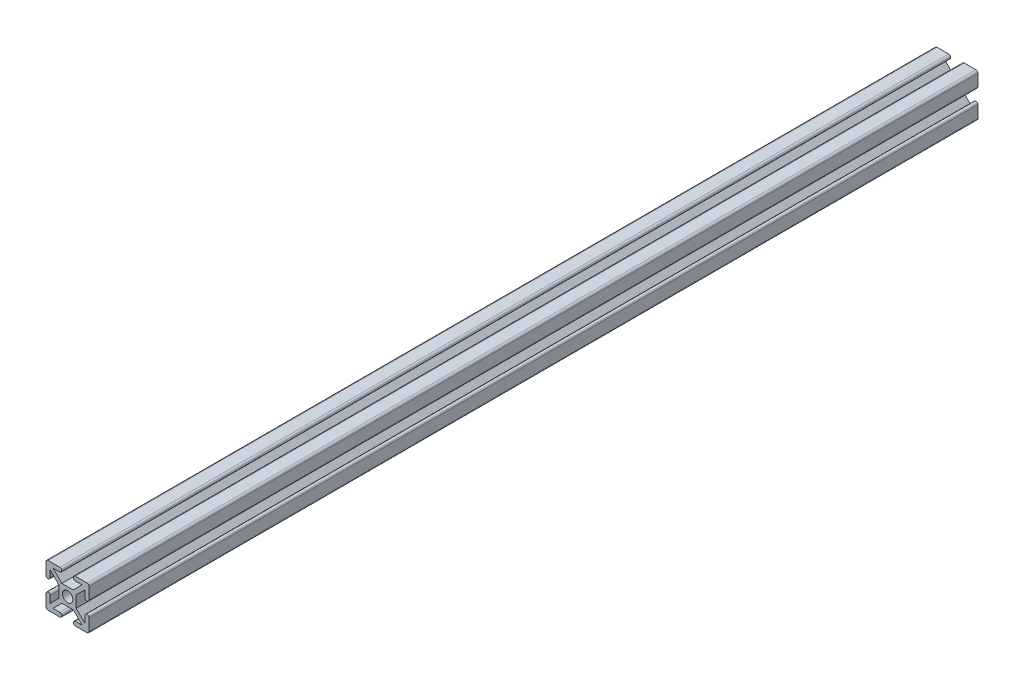
SolidWorks part; units mm, degrees
ref_plane "Alzado" through (0, 0, 0) normal (0, 0, 1) x (1, 0, 0)
ref_plane "Planta" through (0, 0, 0) normal (0, 1, 0) x (1, 0, 0)
ref_plane "Vista lateral" through (0, 0, 0) normal (1, 0, 0) x (0, 0, -1)
sketch "Croquis1" plane through (0, 0, 0) normal (0, 0, 1) x (1, 0, 0)
  line L0 (-16.9501, 14.578) -> (-16.9501, 16.003) construction
  line L1 (2.1027, -1.572) -> (6.8277, -1.572)
  line L2 (-18.3751, 24.153) -> (-18.3751, 16.003)
  line L3 (-16.9501, 25.578) -> (-8.8001, 25.578)
  line L4 (2.0499, 25.578) -> (10.1999, 25.578)
  line L5 (-13.4723, -1.572) -> (-8.7473, -1.572)
  line L6 (-9.3751, 14.578) -> (-9.3751, 6.578)
  line L7 (-18.3223, 5.153) -> (-18.3223, -2.997)
  line L8 (-16.9237, -4.3955) -> (-8.7473, -4.422)
  line L9 (11.6249, 24.153) -> (11.6249, 16.1067)
  line L10 (-15.5251, 20.728) -> (-15.5251, 16.003)
  line L11 (11.6249, 5.2567) -> (11.6249, -2.997)
  line L12 (-7.3751, 24.153) -> (-8.8001, 24.153) construction
  line L13 (2.1027, -4.422) -> (10.1999, -4.422)
  line L14 (-13.5251, 22.728) -> (-8.8001, 22.728)
  line L15 (-15.5251, 5.153) -> (-15.5251, 0.428)
  line L16 (0.6249, 24.153) -> (2.0499, 24.153) construction
  line L17 (2.0499, 22.728) -> (6.7749, 22.728)
  line L18 (10.1999, 14.6817) -> (10.1999, 16.1067) construction
  line L19 (-7.3751, 16.578) -> (-13.5251, 22.728)
  line L20 (8.7749, 20.728) -> (8.7749, 16.1067)
  line L21 (10.1999, 6.6817) -> (10.1999, 5.2567) construction
  line L22 (-9.3751, 14.578) -> (-15.5251, 20.728)
  line L23 (8.7749, 5.2567) -> (8.7749, 0.428)
  line L24 (0.6777, -2.997) -> (2.1027, -2.997) construction
  line L25 (-9.3751, 6.578) -> (-15.5251, 0.428)
  line L26 (-7.3751, 16.578) -> (0.6249, 16.578)
  line L27 (0.6249, 16.578) -> (6.7749, 22.728)
  line L28 (-16.9237, 6.578) -> (-16.9237, 5.153) construction
  line L29 (-13.4723, -1.572) -> (-7.3223, 4.578)
  line L30 (-7.3223, 4.578) -> (0.6777, 4.578)
  line L31 (0.6777, 4.578) -> (6.8277, -1.572)
  line L32 (-7.3223, -2.997) -> (-8.7473, -2.997) construction
  line L33 (2.6249, 6.578) -> (8.7749, 0.428)
  line L34 (2.6249, 14.578) -> (8.7749, 20.728)
  line L35 (2.6249, 14.578) -> (2.6249, 6.578)
  circle A0 centre (-3.3223, 10.578) radius 3.645
  arc A1 (-18.3751, 16.003) -> (-15.5251, 16.003) centre (-16.9501, 16.003) ccw
  arc A2 (-8.8001, 22.728) -> (-8.8001, 25.578) centre (-8.8001, 24.153) ccw
  arc A3 (2.0499, 25.578) -> (2.0499, 22.728) centre (2.0499, 24.153) ccw
  arc A4 (8.7749, 16.1067) -> (11.6249, 16.1067) centre (10.1999, 16.1067) ccw
  arc A5 (11.6249, 5.2567) -> (8.7749, 5.2567) centre (10.1999, 5.2567) ccw
  arc A6 (2.1027, -1.572) -> (2.1027, -4.422) centre (2.1027, -2.997) ccw
  arc A7 (-15.5251, 5.153) -> (-18.3223, 5.153) centre (-16.9237, 5.153) ccw
  arc A8 (-8.7473, -4.422) -> (-8.7473, -1.572) centre (-8.7473, -2.997) ccw
  arc A9 (-18.3223, -2.997) -> (-16.9237, -4.3955) centre (-16.9237, -2.997) ccw
  arc A10 (10.1999, -4.422) -> (11.6249, -2.997) centre (10.1999, -2.997) ccw
  arc A11 (11.6249, 24.153) -> (10.1999, 25.578) centre (10.1999, 24.153) ccw
  arc A12 (-16.9501, 25.578) -> (-18.3751, 24.153) centre (-16.9501, 24.153) ccw
  dimension "D1" = 7.29
  dimension "D2" = 1.425
  dimension "D3" = 1.425
  dimension "D4" = 1.425
  dimension "D5" = 1.425
  dimension "D6" = 1.425
  dimension "D7" = 1.425
  dimension "D8" = 1.425
  dimension "D9" = 1.425
extrude "Saliente-Extruir1" add sketch "Croquis1" along normal blind 619.12
